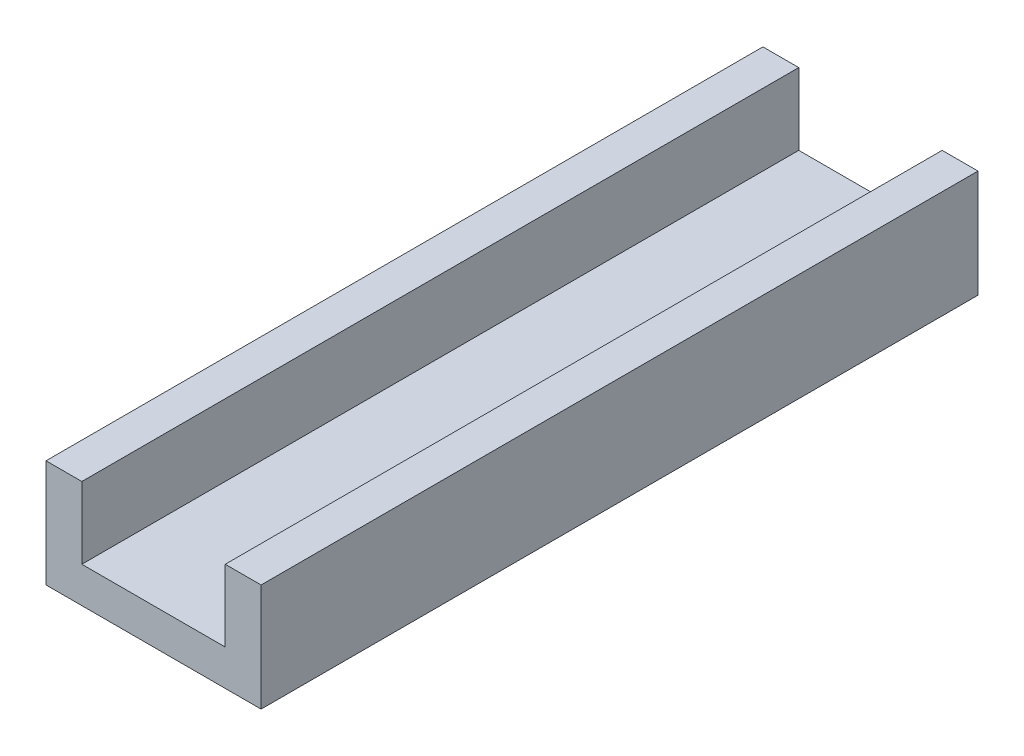
SolidWorks part; units mm, degrees
ref_plane "Front Plane" through (0, 0, 0) normal (0, 0, 1) x (1, 0, 0)
ref_plane "Top Plane" through (0, 0, 0) normal (0, 1, 0) x (1, 0, 0)
ref_plane "Right Plane" through (0, 0, 0) normal (1, 0, 0) x (0, 0, -1)
sketch "Sketch1" plane through (0, 0, 0) normal (0, 0, 1) x (1, 0, 0)
  line L0 (0, 30) -> (0, 0)
  line L1 (0, 0) -> (60, 0)
  line L2 (60, 0) -> (60, 30)
  dimension "D1" = 60
  dimension "D2" = 30
extrude "Extrude-Thin1" add sketch "Sketch1" along normal blind 200 thin thin type one direction reverse wall 10
